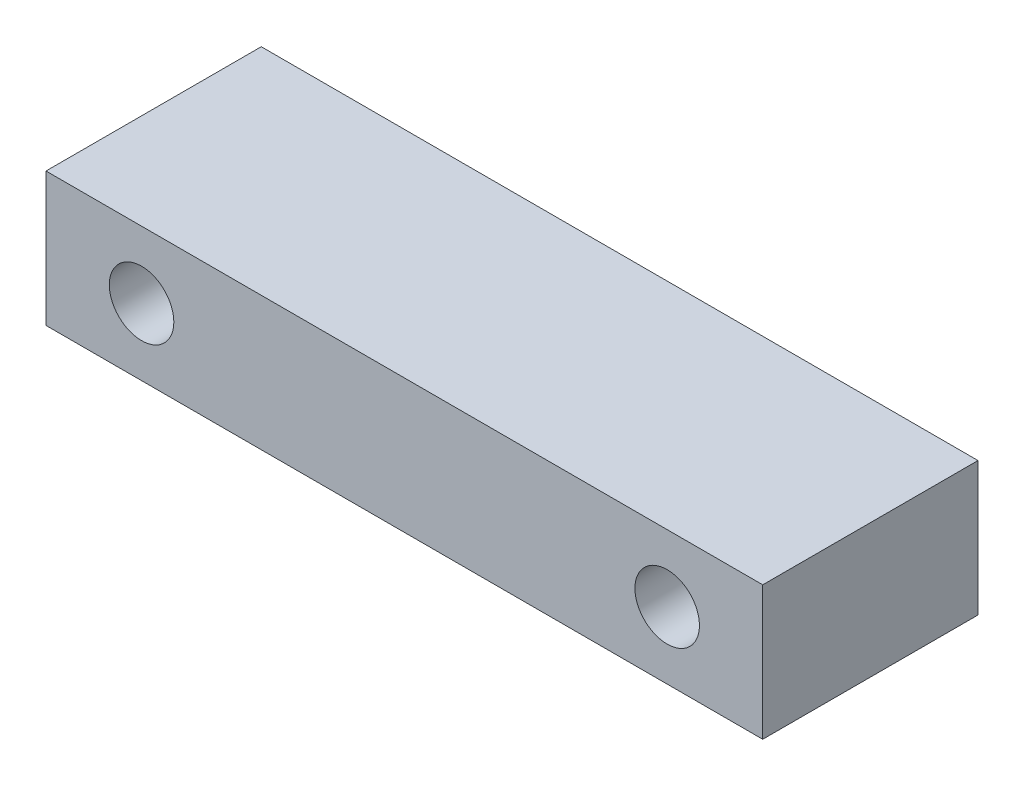
SolidWorks part; units mm, degrees
ref_plane "前视基准面" through (0, 0, 0) normal (0, 0, 1) x (1, 0, 0)
ref_plane "上视基准面" through (0, 0, 0) normal (0, 1, 0) x (1, 0, 0)
ref_plane "右视基准面" through (0, 0, 0) normal (1, 0, 0) x (0, 0, -1)
sketch "草图1" plane through (0, 0, 0) normal (0, 0, 1) x (1, 0, 0)
  line L0 (-15, 0) -> (25.2, 0) construction
  line L1 (-15, 2.8) -> (15, 2.8)
  line L2 (-15, 2.8) -> (-15, -2.8)
  line L3 (-15, -2.8) -> (15, -2.8)
  line L4 (15, -2.8) -> (15, 2.8)
  line L7 (0, 2.8) -> (0, -2.8) construction
  line L11 (0, -10.3075) -> (0, 7.6126) construction
  circle A0 centre (-11, 0) radius 1.35
  circle A1 centre (11, 0) radius 1.35
  point P0 (0, 0)
  dimension "D3" = 2.7
  dimension "D1" = 30
  dimension "D2" = 5.6
  dimension "D4" = 11
extrude "凸台-拉伸1" add sketch "草图1" along normal blind 9.01
